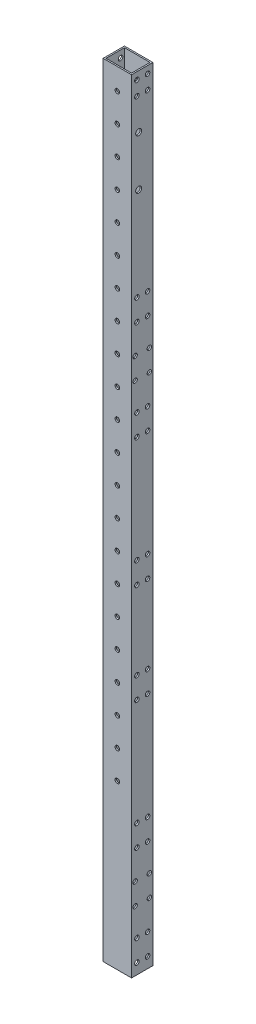
SolidWorks part; units mm, degrees
ref_plane "前视基准面" through (0, 0, 0) normal (0, 0, 1) x (1, 0, 0)
ref_plane "上视基准面" through (0, 0, 0) normal (0, 1, 0) x (1, 0, 0)
ref_plane "右视基准面" through (0, 0, 0) normal (1, 0, 0) x (0, 0, -1)
other "Configuration Table"
sketch "草图1" plane through (0, 0, 0) normal (0, 1, 0) x (1, 0, 0)
  line L1 (-10, -7.5) -> (10, -7.5)
  line L2 (-10, -7.5) -> (-10, 7.5)
  line L3 (-10, 7.5) -> (10, 7.5)
  line L4 (10, -7.5) -> (10, 7.5)
  line L5 (-10, -7.5) -> (10, 7.5) construction
  line L6 (-10, 7.5) -> (10, -7.5) construction
  point P0 (0, 0)
  dimension "D1" = 15
  dimension "D2" = 20
extrude "拉伸-薄壁1" add sketch "草图1" along normal blind 550 thin thin type one direction reverse wall 1
sketch "草图3" plane through (0, 0, -7.5) normal (0, 0, -1) x (-1, 0, 0)
  line L0 (-10, 550) -> (-10, 0) construction
  line L1 (10, 0) -> (-10, 0)
  line L2 (10, 0) -> (10, 100)
  line L3 (10, 100) -> (-10, 100)
  line L4 (-10, 0) -> (-10, 100)
  dimension "D1" = 100
sketch "草图4" plane through (-10, 0, 0) normal (-1, 0, 0) x (0, 0, 1)
  line L0 (7.5, 550) -> (7.5, 0) construction
  line L1 (-7.5, 550) -> (7.5, 550) construction
  line L2 (-7.5, 550) -> (-7.5, 530) construction
  line L3 (-7.5, 530) -> (7.5, 530) construction
  line L4 (7.5, 550) -> (7.5, 530) construction
  line L5 (-7.5, 540) -> (7.5, 540) construction
  line L6 (0, 550) -> (0, 530) construction
  circle A0 centre (-3.75, 545) radius 1.6
  circle A1 centre (-3.75, 535) radius 1.6
  circle A2 centre (3.75, 535) radius 1.6
  circle A3 centre (3.75, 545) radius 1.6
  dimension "D2" = 3.2
  dimension "D1" = 20
  dimension "D3" = 3.75
  dimension "D4" = 5
extrude "切除-拉伸1" cut sketch "草图4" against normal through all
sketch "草图5" plane through (-10, 0, 0) normal (-1, 0, 0) x (0, 0, 1)
  line L0 (7.5, 550) -> (7.5, 0) construction
  line L1 (-7.5, 550) -> (7.5, 550) construction
  line L2 (-7.5, 550) -> (-7.5, 530) construction
  line L3 (-7.5, 530) -> (7.5, 530) construction
  line L4 (7.5, 550) -> (7.5, 530) construction
  line L5 (2.5, 512.5) -> (2.5, 477.5) construction
  line L6 (-7.5, 530) -> (7.5, 530) construction
  line L7 (-7.5, 530) -> (-7.5, 520) construction
  line L8 (-7.5, 520) -> (7.5, 520) construction
  line L9 (7.5, 530) -> (7.5, 520) construction
  line L10 (-7.5, 520) -> (7.5, 520) construction
  line L11 (-7.5, 520) -> (-7.5, 500) construction
  line L12 (-7.5, 500) -> (7.5, 500) construction
  line L13 (7.5, 520) -> (7.5, 500) construction
  circle A0 centre (2.5, 512.5) radius 2.1
  circle A1 centre (2.5, 477.5) radius 2.1
  dimension "D4" = 4.2
  dimension "D7" = 4.2
  dimension "D1" = 20
  dimension "D2" = 10
  dimension "D3" = 20
  dimension "D5" = 5
  dimension "D6" = 7.5
  dimension "D8" = 35
extrude "切除-拉伸2" cut sketch "草图5" against normal through all
sketch "草图6" plane through (10, 0, 0) normal (1, 0, 0) x (0, 0, -1)
  line L0 (-7.5, 550) -> (-7.5, 0) construction
  line L1 (7.5, 0) -> (-7.5, 0) construction
  line L2 (7.5, 0) -> (7.5, 100) construction
  line L3 (7.5, 100) -> (-7.5, 100) construction
  line L4 (-7.5, 0) -> (-7.5, 100) construction
  line L5 (0, 100) -> (0, 0) construction
  line L6 (-7.5, 50) -> (7.5, 50) construction
  line L7 (-7.5, 15) -> (7.5, 15) construction
  line L8 (7.5, 0) -> (-7.5, 0) construction
  line L9 (7.5, 0) -> (7.5, 30) construction
  line L10 (7.5, 30) -> (-7.5, 30) construction
  line L11 (-7.5, 0) -> (-7.5, 30) construction
  line L12 (7.5, 160) -> (-7.5, 160) construction
  line L13 (7.5, 160) -> (7.5, 260) construction
  line L14 (7.5, 260) -> (-7.5, 260) construction
  line L15 (-7.5, 160) -> (-7.5, 260) construction
  line L16 (0, 260) -> (0, 160) construction
  line L17 (-7.5, 210) -> (7.5, 210) construction
  line L18 (-7.5, 175) -> (7.5, 175) construction
  line L19 (7.5, 160) -> (-7.5, 160) construction
  line L20 (7.5, 160) -> (7.5, 190) construction
  line L21 (7.5, 190) -> (-7.5, 190) construction
  line L22 (-7.5, 160) -> (-7.5, 190) construction
  line L23 (7.5, 320) -> (-7.5, 320) construction
  line L24 (7.5, 320) -> (7.5, 420) construction
  line L25 (7.5, 420) -> (-7.5, 420) construction
  line L26 (-7.5, 320) -> (-7.5, 420) construction
  line L27 (0, 420) -> (0, 320) construction
  line L28 (-7.5, 370) -> (7.5, 370) construction
  line L29 (-7.5, 335) -> (7.5, 335) construction
  line L30 (7.5, 320) -> (-7.5, 320) construction
  line L31 (7.5, 320) -> (7.5, 350) construction
  line L32 (7.5, 350) -> (-7.5, 350) construction
  line L33 (-7.5, 320) -> (-7.5, 350) construction
  circle A0 centre (-3.75, 7.5) radius 1.6
  circle A1 centre (-3.75, 22.5) radius 1.6
  circle A2 centre (3.75, 7.5) radius 1.6
  circle A3 centre (3.75, 22.5) radius 1.6
  circle A4 centre (-3.75, 92.5) radius 1.6
  circle A5 centre (3.75, 92.5) radius 1.6
  circle A6 centre (3.75, 77.5) radius 1.6
  circle A7 centre (-3.75, 77.5) radius 1.6
  circle A8 centre (-3.75, 167.5) radius 1.6
  circle A9 centre (-3.75, 182.5) radius 1.6
  circle A10 centre (3.75, 167.5) radius 1.6
  circle A11 centre (3.75, 182.5) radius 1.6
  circle A12 centre (-3.75, 252.5) radius 1.6
  circle A13 centre (3.75, 252.5) radius 1.6
  circle A14 centre (3.75, 237.5) radius 1.6
  circle A15 centre (-3.75, 237.5) radius 1.6
  circle A16 centre (-3.75, 327.5) radius 1.6
  circle A17 centre (-3.75, 342.5) radius 1.6
  circle A18 centre (3.75, 327.5) radius 1.6
  circle A19 centre (3.75, 342.5) radius 1.6
  circle A20 centre (-3.75, 412.5) radius 1.6
  circle A21 centre (3.75, 412.5) radius 1.6
  circle A22 centre (3.75, 397.5) radius 1.6
  circle A23 centre (-3.75, 397.5) radius 1.6
  dimension "D5" = 3.2
  dimension "D1" = 100
  dimension "D2" = 30
  dimension "D3" = 3.75
  dimension "D4" = 7.5
  dimension "D6" = 3
extrude "切除-拉伸3" cut sketch "草图6" against normal through all
sketch "草图7" plane through (0, 0, -7.5) normal (0, 0, -1) x (-1, 0, 0)
  line L0 (0, 100) -> (0, 115) construction
  line L1 (10, 100) -> (-10, 100) construction
  circle A0 centre (0, 115) radius 1.6
  circle A1 centre (0, 135) radius 1.6
  circle A2 centre (0, 155) radius 1.6
  circle A3 centre (0, 175) radius 1.6
  circle A4 centre (0, 195) radius 1.6
  circle A5 centre (0, 215) radius 1.6
  circle A6 centre (0, 235) radius 1.6
  circle A7 centre (0, 255) radius 1.6
  circle A8 centre (0, 275) radius 1.6
  circle A9 centre (0, 295) radius 1.6
  circle A10 centre (0, 315) radius 1.6
  circle A11 centre (0, 335) radius 1.6
  circle A12 centre (0, 355) radius 1.6
  circle A13 centre (0, 375) radius 1.6
  circle A14 centre (0, 395) radius 1.6
  circle A15 centre (0, 415) radius 1.6
  circle A16 centre (0, 435) radius 1.6
  circle A17 centre (0, 455) radius 1.6
  circle A18 centre (0, 475) radius 1.6
  circle A19 centre (0, 495) radius 1.6
  circle A20 centre (0, 515) radius 1.6
  circle A21 centre (0, 535) radius 1.6
  dimension "D1" = 3.2
  dimension "D2" = 15
  dimension "D3" = 22
extrude "切除-拉伸4" cut sketch "草图7" against normal through all
sketch "草图8" plane through (10, 0, 0) normal (1, 0, 0) x (0, 0, -1)
  line L0 (0, -1.3576) -> (0, 550) construction
  line L1 (-7.5, 550) -> (7.5, 550) construction
  line L2 (-7.5, 370) -> (7.5, 370) construction
  line L3 (-7.5, 550) -> (-7.5, 0) construction
  line L4 (7.5, 550) -> (7.5, 0) construction
  line L5 (-7.5, 0) -> (7.5, 0) construction
  line L6 (0, -321.3576) -> (0, 230) construction
  line L7 (-7.5, 50) -> (7.5, 50) construction
  circle A0 centre (5, 377.5) radius 1.55
  circle A1 centre (-5, 377.5) radius 1.55
  circle A2 centre (5, 362.5) radius 1.55
  circle A3 centre (-5, 362.5) radius 1.55
  circle A4 centre (5, 57.5) radius 1.55
  circle A5 centre (-5, 57.5) radius 1.55
  circle A6 centre (5, 42.5) radius 1.55
  circle A7 centre (-5, 42.5) radius 1.55
  dimension "D2" = 3.1
  dimension "D1" = 370
  dimension "D3" = 15
  dimension "D4" = 10
  dimension "D5" = 2
extrude "切除-拉伸5" cut sketch "草图8" against normal through all
